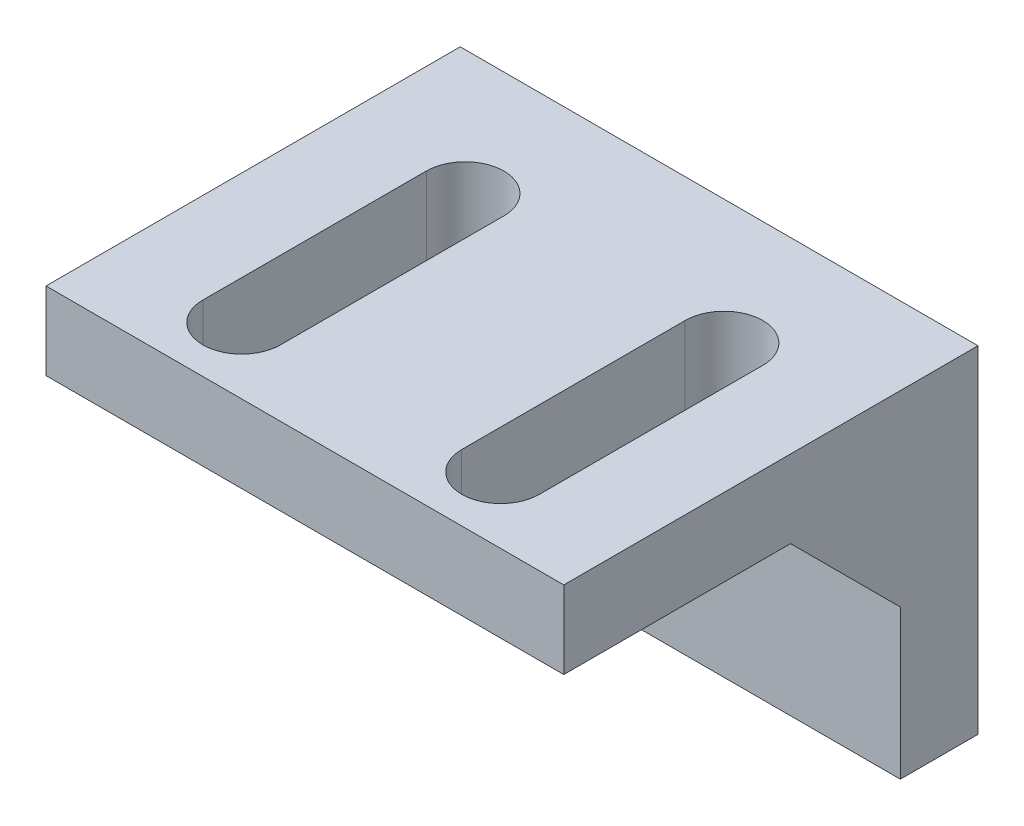
SolidWorks part; units mm, degrees
ref_plane "Front Plane" through (0, 0, 0) normal (0, 0, 1) x (1, 0, 0)
ref_plane "Top Plane" through (0, 0, 0) normal (0, 1, 0) x (1, 0, 0)
ref_plane "Right Plane" through (0, 0, 0) normal (1, 0, 0) x (0, 0, -1)
sketch "Sketch1" plane through (0, 0, 0) normal (0, 0, 1) x (1, 0, 0)
  line L1 (14.8868, -20.555) -> (34.8868, -20.555)
  line L2 (14.8868, -20.555) -> (14.8868, -33.555)
  line L3 (14.8868, -33.555) -> (34.8868, -33.555)
  line L4 (34.8868, -20.555) -> (34.8868, -33.555)
  line L5 (35, -20.555) -> (-35, -20.555) construction
  line L6 (34.8868, -14.155) -> (34.8868, -20.555) construction
  line L7 (14.8868, -14.155) -> (14.8868, -20.555) construction
  dimension "D1" = 13
extrude "Boss-Extrude1" add sketch "Sketch1" along normal blind 3 contours L3 L4 L1 L2
sketch "Sketch2" plane through (0, 0, 3) normal (0, 0, 1) x (1, 0, 0)
  line L0 (34.8868, -20.555) -> (34.8868, -33.555) construction
  line L1 (14.8868, -20.555) -> (34.8868, -20.555)
  line L2 (14.8868, -20.555) -> (14.8868, -23.555)
  line L3 (14.8868, -23.555) -> (34.8868, -23.555)
  line L4 (34.8868, -20.555) -> (34.8868, -23.555)
  dimension "D1" = 3
extrude "Boss-Extrude2" add sketch "Sketch2" along normal blind 13
sketch "Sketch3" plane through (34.8868, 0, 0) normal (1, 0, 0) x (0, 0, -1)
  line L0 (-7.2391, -23.555) -> (-3, -27.7941)
  line L3 (-3, -27.7941) -> (-3, -23.555)
  line L4 (-3, -23.555) -> (-7.2391, -23.555)
  line L5 (-16, -23.555) -> (-3, -23.555) construction
  line L6 (-3, -23.555) -> (-3, -33.555) construction
extrude "Boss-Extrude3" add sketch "Sketch3" against normal blind 3
sketch "Sketch4" plane through (0, -23.555, 0) normal (0, -1, 0) x (1, 0, 0)
  line L0 (24.8868, 16) -> (24.8868, 3) construction
  line L1 (14.8868, 16) -> (34.8868, 16) construction
  line L2 (14.8868, 3) -> (31.8868, 3) construction
  line L3 (29.8868, 4.8121) -> (29.8868, 13.4412) construction
  line L4 (28.3868, 4.8121) -> (28.3868, 13.4412)
  line L5 (31.3868, 4.8121) -> (31.3868, 13.4412)
  arc A0 (28.3868, 4.8121) -> (31.3868, 4.8121) centre (29.8868, 4.8121) ccw
  arc A1 (31.3868, 13.4412) -> (28.3868, 13.4412) centre (29.8868, 13.4412) ccw
  point P8 (29.8868, 9.1266)
  dimension "D1" = 1.5
  dimension "D2" = 5
extrude "Cut-Extrude1" cut sketch "Sketch4" against normal through all contours A1 L4 A0 L5
ref_plane "Plane1" through (24.8868, 0, 0) normal (-1, 0, 0) x (0, 0, 1)
mirror "Mirror1" about plane through (24.8868, 0, 0) normal (-1, 0, 0) of "Boss-Extrude3", "Cut-Extrude1"
